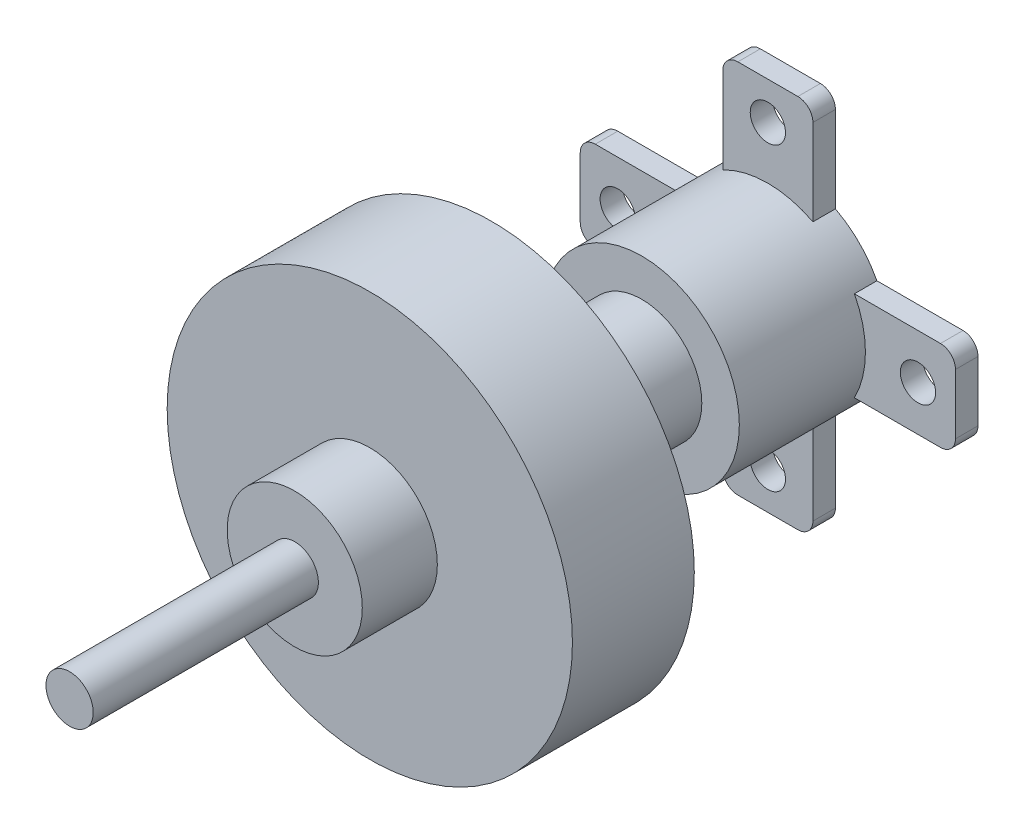
SolidWorks part; units mm, degrees
ref_plane "Alzado" through (0, 0, 0) normal (0, 0, 1) x (1, 0, 0)
ref_plane "Planta" through (0, 0, 0) normal (0, 1, 0) x (1, 0, 0)
ref_plane "Vista lateral" through (0, 0, 0) normal (1, 0, 0) x (0, 0, -1)
sketch "Croquis1" plane through (0, 0, 0) normal (0, 0, 1) x (1, 0, 0)
  circle A0 centre (0, 0) radius 4
  circle A1 centre (0, 0) radius 6.5
  dimension "D1" = 8
  dimension "D2" = 13
extrude "Saliente-Extruir1" add sketch "Croquis1" along normal blind 8.4
sketch "Croquis2" plane through (0, 0, 8.4) normal (0, 0, 1) x (1, 0, 0)
  circle A0 centre (0, 0) radius 4
extrude "Saliente-Extruir2" add sketch "Croquis2" along normal blind 10 separate body
sketch "Croquis3" plane through (0, 0, 18.4) normal (0, 0, 1) x (1, 0, 0)
  circle A0 centre (0, 0) radius 13.5
  dimension "D1" = 27
extrude "Saliente-Extruir3" add sketch "Croquis3" along normal blind 8.12
sketch "Croquis4" plane through (0, 0, 26.52) normal (0, 0, 1) x (1, 0, 0)
  circle A0 centre (0, 0) radius 4.5
  dimension "D1" = 9
extrude "Saliente-Extruir4" add sketch "Croquis4" along normal blind 5
sketch "Croquis5" plane through (0, 0, 31.52) normal (0, 0, 1) x (1, 0, 0)
  circle A0 centre (0, 0) radius 1.575
  dimension "D1" = 3.15
extrude "Saliente-Extruir5" add sketch "Croquis5" along normal blind 15
sketch "Croquis6" plane through (0, 0, 0) normal (0, 0, -1) x (-1, 0, 0)
  line L0 (0, 0) -> (0, -19.3406) construction
  line L1 (-2, -12.5) -> (2, -12.5)
  line L2 (3, -11.5) -> (3, -5.7663)
  line L3 (0, -6.5) -> (3, -6.5) construction
  line L4 (-3, -11.5) -> (-3, -5.7663)
  line L5 (-11.5, -3) -> (-5.7663, -3)
  line L6 (-12.5, 2) -> (-12.5, -2)
  line L7 (-11.5, 3) -> (-5.7663, 3)
  line L8 (-3, 11.5) -> (-3, 5.7663)
  line L9 (2, 12.5) -> (-2, 12.5)
  line L10 (3, 11.5) -> (3, 5.7663)
  line L11 (11.5, 3) -> (5.7663, 3)
  line L12 (12.5, -2) -> (12.5, 2)
  line L13 (11.5, -3) -> (5.7663, -3)
  circle A0 centre (0, -10) radius 1.175
  circle A1 centre (0, 0) radius 4 construction
  circle A2 centre (0, 0) radius 6.5 construction
  arc A3 (-2, -12.5) -> (-3, -11.5) centre (-2, -11.5) cw
  arc A4 (2, -12.5) -> (3, -11.5) centre (2, -11.5) ccw
  arc A5 (-12.5, -2) -> (-11.5, -3) centre (-11.5, -2) ccw
  arc A6 (-12.5, 2) -> (-11.5, 3) centre (-11.5, 2) cw
  circle A7 centre (-10, 0) radius 1.175
  arc A8 (-2, 12.5) -> (-3, 11.5) centre (-2, 11.5) ccw
  arc A9 (2, 12.5) -> (3, 11.5) centre (2, 11.5) cw
  circle A10 centre (0, 10) radius 1.175
  arc A11 (12.5, 2) -> (11.5, 3) centre (11.5, 2) ccw
  arc A12 (12.5, -2) -> (11.5, -3) centre (11.5, -2) cw
  circle A13 centre (10, 0) radius 1.175
  arc A14 (3, 5.7663) -> (5.7663, 3) centre (0, 0) cw
  arc A15 (5.7663, -3) -> (3, -5.7663) centre (0, 0) cw
  arc A16 (-3, -5.7663) -> (-5.7663, -3) centre (0, 0) cw
  arc A17 (-5.7663, 3) -> (-3, 5.7663) centre (0, 0) cw
  point P15 (0, -12.5)
  point P18 (-3, -12.5)
  point P21 (3, -12.5)
  dimension "D1" = 2.35
  dimension "D2" = 10
  dimension "D5" = 1
  dimension "D3" = 3
  dimension "D4" = 6
  dimension "D6" = 4
  dimension "D7" = 4
extrude "Saliente-Extruir6" add sketch "Croquis6" along normal blind 1.5
